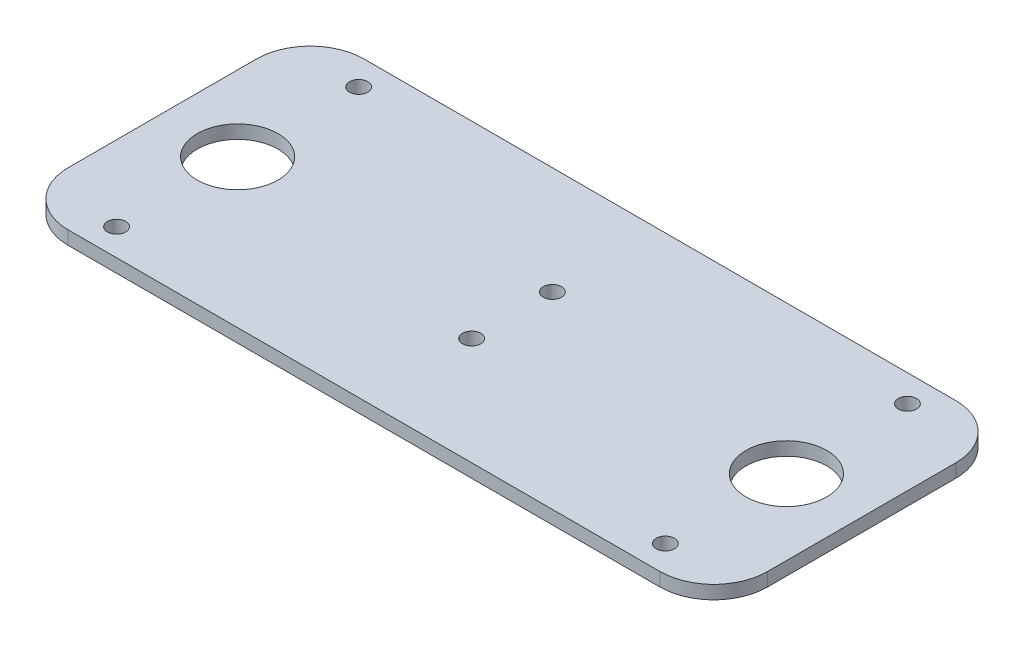
SolidWorks part; units mm, degrees
ref_plane "Front Plane" through (0, 0, 0) normal (0, 0, 1) x (1, 0, 0)
ref_plane "Top Plane" through (0, 0, 0) normal (0, 1, 0) x (1, 0, 0)
ref_plane "Right Plane" through (0, 0, 0) normal (1, 0, 0) x (0, 0, -1)
sketch "Sketch1" plane through (0, 0, 0) normal (0, 1, 0) x (1, 0, 0)
  line L1 (10, 0) -> (120, 0)
  line L2 (0, 10) -> (0, 45)
  line L3 (10, 55) -> (120, 55)
  line L4 (130, 10) -> (130, 45)
  arc A0 (10, 55) -> (0, 45) centre (10, 45) ccw
  arc A1 (0, 10) -> (10, 0) centre (10, 10) ccw
  arc A2 (130, 10) -> (120, 0) centre (120, 10) cw
  arc A3 (120, 55) -> (130, 45) centre (120, 45) cw
  point P7 (0, 55)
  point P10 (0, 0)
  point P13 (130, 0)
  dimension "D3" = 10
  dimension "D4" = 10
  dimension "D5" = 10
  dimension "D6" = 10
  dimension "D1" = 130
  dimension "D2" = 55
extrude "Boss-Extrude1" add sketch "Sketch1" along normal blind 2.5
sketch "Sketch2" plane through (0, 2.5, 0) normal (0, 1, 0) x (1, 0, 0)
  line L3 (65, 53.2946) -> (65, -1.7054) construction
  line L4 (14, 27.5) -> (116, 27.5) construction
  circle A0 centre (14, 5) radius 1.7
  circle A1 centre (14, 50) radius 1.7
  circle A2 centre (116, 5) radius 1.7
  circle A3 centre (116, 50) radius 1.7
  circle A4 centre (14, 27.5) radius 7.5
  circle A5 centre (116, 27.5) radius 7.5
  circle A6 centre (65, 35) radius 1.7
  circle A7 centre (65, 20) radius 1.7
extrude "Cut-Extrude1" cut sketch "Sketch2" against normal through all
